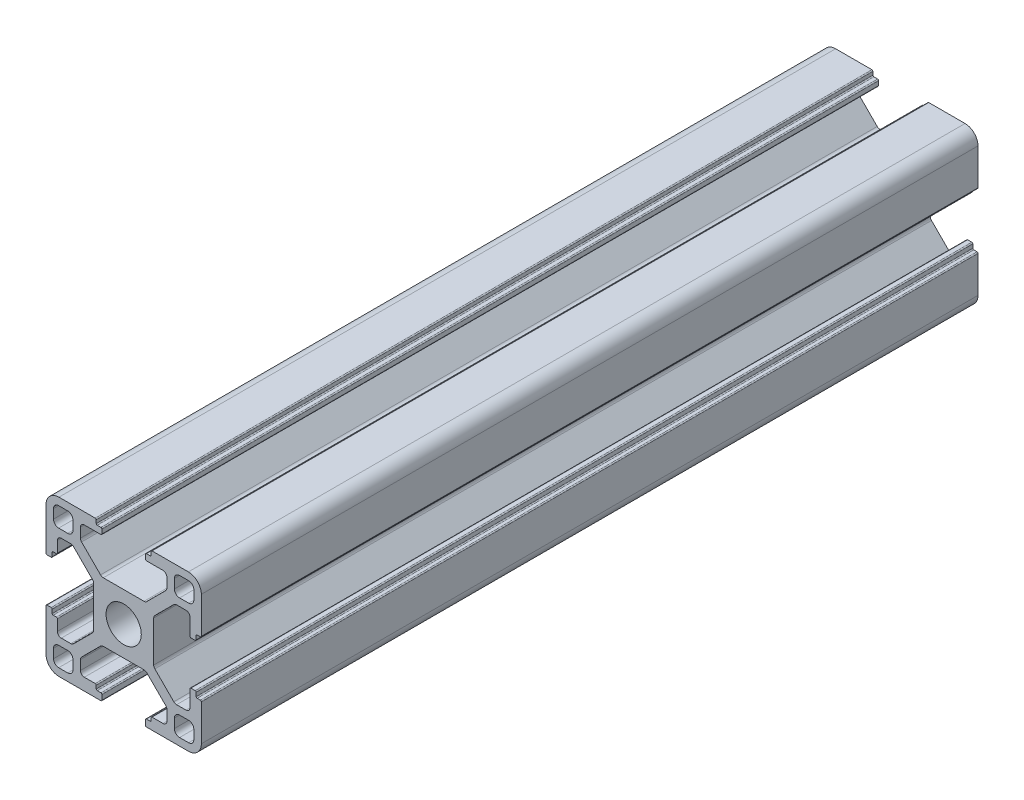
SolidWorks part; units mm, degrees
material "6063-T5"
ref_plane "Front Plane" through (0, 0, 0) normal (0, 0, 1) x (1, 0, 0)
ref_plane "Top Plane" through (0, 0, 0) normal (0, 1, 0) x (1, 0, 0)
ref_plane "Right Plane" through (0, 0, 0) normal (1, 0, 0) x (0, 0, -1)
sketch "Sketch1" plane through (0, 0, 0) normal (0, 0, 1) x (1, 0, 0)
  line L0 (0, 2.5) -> (0, 10.6)
  line L1 (2.5, 30) -> (9.5, 30)
  line L2 (30, 27.5) -> (30, 20.5)
  line L3 (27.5, 0) -> (19.4, 0)
  line L4 (19.464, 9.1128) -> (23.1303, 5.4465)
  line L5 (21.0197, 10.536) -> (24.686, 6.8697)
  line L6 (10.536, 21.0197) -> (6.8697, 24.686)
  line L7 (8.9803, 19.464) -> (5.314, 23.1303)
  line L8 (11.0663, 20.8) -> (18.9337, 20.8)
  line L9 (20.8, 18.9337) -> (20.8, 11.0663)
  line L10 (18.9337, 9.3324) -> (11.0663, 9.3324)
  line L11 (9.2, 11.0663) -> (9.2, 18.9337)
  line L12 (0, 19.4) -> (0, 27.5)
  line L13 (30, 9.5) -> (30, 2.5)
  line L14 (19.4, 27.8) -> (22.6, 27.8)
  line L15 (10.6, 27.8) -> (7.4, 27.8)
  line L16 (10.6, 0) -> (2.5, 0)
  line L17 (2.2, 20.5) -> (2.2, 22.6)
  line L18 (2.2, 9.5) -> (2.2, 7.4)
  line L19 (9.5, 2.3324) -> (7.4, 2.3324)
  line L20 (19.464, 21.0197) -> (23.1303, 24.686)
  line L21 (21.0197, 19.464) -> (24.686, 23.1303)
  line L22 (8.9803, 10.536) -> (5.314, 6.8697)
  line L23 (10.536, 9.1128) -> (6.8697, 5.4465)
  line L24 (10.8, 28.8) -> (10.8, 28)
  line L25 (19.2, 28.8) -> (19.2, 28)
  line L26 (0.2, 19.2) -> (1, 19.2)
  line L27 (0.2, 10.8) -> (1, 10.8)
  line L28 (28.8, 19.2) -> (28, 19.2)
  line L29 (28.8, 10.8) -> (28, 10.8)
  line L30 (10.8, 0.2) -> (10.8, 1.1324)
  line L31 (19.2, 0.2) -> (19.2, 1.1324)
  line L32 (20.5, 30) -> (27.5, 30)
  line L33 (27.8, 19.4) -> (27.8, 22.6)
  line L34 (27.8, 10.6) -> (27.8, 7.4)
  line L35 (20.5, 2.2) -> (22.6, 2.2)
  line L36 (6.65, 27.05) -> (6.65, 25.2163)
  line L37 (23.35, 27.05) -> (23.35, 25.2163)
  line L38 (2.95, 23.35) -> (4.7837, 23.35)
  line L39 (27.05, 23.35) -> (25.2163, 23.35)
  line L40 (2.95, 6.65) -> (4.7837, 6.65)
  line L41 (6.65, 3.0824) -> (6.65, 4.9161)
  line L42 (23.35, 2.95) -> (23.35, 4.9161)
  line L43 (27.05, 6.65) -> (25.2163, 6.65)
  line L44 (29, 10.6) -> (29, 9.9)
  line L45 (29.8, 20.3) -> (29.2, 20.3)
  line L46 (29, 20.1) -> (29, 19.4)
  line L47 (29.2, 9.7) -> (29.8, 9.7)
  line L48 (19.4, 29) -> (20.1, 29)
  line L49 (9.7, 29.8) -> (9.7, 29.2)
  line L50 (9.9, 29) -> (10.6, 29)
  line L51 (20.3, 29.2) -> (20.3, 29.8)
  line L52 (9.7, 2.1324) -> (9.7, 1.5324)
  line L53 (9.9, 1.3324) -> (10.6, 1.3324)
  line L54 (19.4, 1.3324) -> (20.1, 1.3324)
  line L55 (20.3, 1.5324) -> (20.3, 2)
  line L56 (2, 20.3) -> (1.4, 20.3)
  line L57 (1.2, 20.1) -> (1.2, 19.4)
  line L58 (1.2, 10.6) -> (1.2, 9.9)
  line L59 (1.4, 9.7) -> (2, 9.7)
  line L60 (27.55, 1.45) -> (25.8, 1.45)
  line L61 (24.8, 2.45) -> (24.8, 4.2)
  line L62 (25.8, 5.2) -> (27.55, 5.2)
  line L63 (28.55, 4.2) -> (28.55, 2.45)
  line L64 (24.8, 25.8) -> (24.8, 27.55)
  line L65 (25.8, 28.55) -> (27.55, 28.55)
  line L66 (28.55, 27.55) -> (28.55, 25.8)
  line L67 (27.55, 24.8) -> (25.8, 24.8)
  line L68 (2.45, 28.55) -> (4.2, 28.55)
  line L69 (5.2, 27.55) -> (5.2, 25.8)
  line L70 (1.45, 2.45) -> (1.45, 4.2)
  line L71 (2.45, 5.2) -> (4.2, 5.2)
  line L72 (5.2, 4.2) -> (5.2, 2.45)
  line L73 (4.2, 1.45) -> (2.45, 1.45)
  line L74 (4.2, 24.8) -> (2.45, 24.8)
  line L75 (1.45, 25.8) -> (1.45, 27.55)
  circle A0 centre (15, 15) radius 3.4
  arc A1 (25.8, 1.45) -> (24.8, 2.45) centre (25.8, 2.45) cw
  arc A2 (27.55, 1.45) -> (28.55, 2.45) centre (27.55, 2.45) ccw
  arc A3 (27.55, 5.2) -> (28.55, 4.2) centre (27.55, 4.2) cw
  arc A4 (24.8, 4.2) -> (25.8, 5.2) centre (25.8, 4.2) cw
  arc A5 (1.45, 2.45) -> (2.45, 1.45) centre (2.45, 2.45) ccw
  arc A6 (5.2, 2.45) -> (4.2, 1.45) centre (4.2, 2.45) cw
  arc A7 (4.2, 5.2) -> (5.2, 4.2) centre (4.2, 4.2) cw
  arc A8 (1.45, 4.2) -> (2.45, 5.2) centre (2.45, 4.2) cw
  arc A9 (24.8, 25.8) -> (25.8, 24.8) centre (25.8, 25.8) ccw
  arc A10 (28.55, 25.8) -> (27.55, 24.8) centre (27.55, 25.8) cw
  arc A11 (27.55, 28.55) -> (28.55, 27.55) centre (27.55, 27.55) cw
  arc A12 (24.8, 27.55) -> (25.8, 28.55) centre (25.8, 27.55) cw
  arc A13 (4.2, 28.55) -> (5.2, 27.55) centre (4.2, 27.55) cw
  arc A14 (5.2, 25.8) -> (4.2, 24.8) centre (4.2, 25.8) cw
  arc A15 (2.45, 24.8) -> (1.45, 25.8) centre (2.45, 25.8) cw
  arc A16 (2.45, 28.55) -> (1.45, 27.55) centre (2.45, 27.55) ccw
  arc A17 (30, 2.5) -> (27.5, 0) centre (27.5, 2.5) cw
  arc A18 (0, 2.5) -> (2.5, 0) centre (2.5, 2.5) ccw
  arc A19 (27.5, 30) -> (30, 27.5) centre (27.5, 27.5) cw
  arc A20 (0, 27.5) -> (2.5, 30) centre (2.5, 27.5) cw
  arc A21 (0, 10.6) -> (0.2, 10.8) centre (0.2, 10.6) cw
  arc A22 (1.2, 10.6) -> (1, 10.8) centre (1, 10.6) ccw
  arc A23 (2, 9.7) -> (2.2, 9.5) centre (2, 9.5) cw
  arc A24 (9.7, 2.1324) -> (9.5, 2.3324) centre (9.5, 2.1324) ccw
  arc A25 (10.6, 1.3324) -> (10.8, 1.1324) centre (10.6, 1.1324) cw
  arc A26 (10.6, 0) -> (10.8, 0.2) centre (10.6, 0.2) ccw
  arc A27 (19.4, 0) -> (19.2, 0.2) centre (19.4, 0.2) cw
  arc A28 (19.4, 1.3324) -> (19.2, 1.1324) centre (19.4, 1.1324) ccw
  arc A29 (20.3, 2) -> (20.5, 2.2) centre (20.5, 2) cw
  arc A30 (28, 10.8) -> (27.8, 10.6) centre (28, 10.6) ccw
  arc A31 (29, 10.6) -> (28.8, 10.8) centre (28.8, 10.6) ccw
  arc A32 (29.8, 9.7) -> (30, 9.5) centre (29.8, 9.5) cw
  arc A33 (28, 19.2) -> (27.8, 19.4) centre (28, 19.4) cw
  arc A34 (29, 19.4) -> (28.8, 19.2) centre (28.8, 19.4) cw
  arc A35 (30, 20.5) -> (29.8, 20.3) centre (29.8, 20.5) cw
  arc A36 (20.3, 29.8) -> (20.5, 30) centre (20.5, 29.8) cw
  arc A37 (19.4, 29) -> (19.2, 28.8) centre (19.4, 28.8) ccw
  arc A38 (19.2, 28) -> (19.4, 27.8) centre (19.4, 28) ccw
  arc A39 (10.8, 28) -> (10.6, 27.8) centre (10.6, 28) cw
  arc A40 (0, 19.4) -> (0.2, 19.2) centre (0.2, 19.4) ccw
  arc A41 (1.2, 19.4) -> (1, 19.2) centre (1, 19.4) cw
  arc A42 (2, 20.3) -> (2.2, 20.5) centre (2, 20.5) ccw
  arc A43 (10.6, 29) -> (10.8, 28.8) centre (10.6, 28.8) cw
  arc A44 (9.5, 30) -> (9.7, 29.8) centre (9.5, 29.8) cw
  arc A45 (1.4, 20.3) -> (1.2, 20.1) centre (1.4, 20.1) ccw
  arc A46 (20.1, 29) -> (20.3, 29.2) centre (20.1, 29.2) ccw
  arc A47 (9.7, 29.2) -> (9.9, 29) centre (9.9, 29.2) ccw
  arc A48 (29.2, 20.3) -> (29, 20.1) centre (29.2, 20.1) ccw
  arc A49 (29, 9.9) -> (29.2, 9.7) centre (29.2, 9.9) ccw
  arc A50 (20.1, 1.3324) -> (20.3, 1.5324) centre (20.1, 1.5324) ccw
  arc A51 (1.2, 9.9) -> (1.4, 9.7) centre (1.4, 9.9) ccw
  arc A52 (9.7, 1.5324) -> (9.9, 1.3324) centre (9.9, 1.5324) ccw
  arc A53 (23.35, 25.2163) -> (23.1303, 24.686) centre (22.6, 25.2163) cw
  arc A54 (25.2163, 23.35) -> (24.686, 23.1303) centre (25.2163, 22.6) ccw
  arc A55 (20.8, 18.9337) -> (21.0197, 19.464) centre (21.55, 18.9337) cw
  arc A56 (18.9337, 20.8) -> (19.464, 21.0197) centre (18.9337, 21.55) ccw
  arc A57 (6.65, 25.2163) -> (6.8697, 24.686) centre (7.4, 25.2163) ccw
  arc A58 (11.0663, 20.8) -> (10.536, 21.0197) centre (11.0663, 21.55) cw
  arc A59 (4.7837, 23.35) -> (5.314, 23.1303) centre (4.7837, 22.6) cw
  arc A60 (9.2, 18.9337) -> (8.9803, 19.464) centre (8.45, 18.9337) ccw
  arc A61 (4.7837, 6.65) -> (5.314, 6.8697) centre (4.7837, 7.4) ccw
  arc A62 (9.2, 11.0663) -> (8.9803, 10.536) centre (8.45, 11.0663) cw
  arc A63 (6.65, 4.9161) -> (6.8697, 5.4465) centre (7.4, 4.9161) cw
  arc A64 (11.0663, 9.3324) -> (10.536, 9.1128) centre (11.0663, 8.5824) ccw
  arc A65 (18.9337, 9.3324) -> (19.464, 9.1128) centre (18.9337, 8.5824) cw
  arc A66 (20.8, 11.0663) -> (21.0197, 10.536) centre (21.55, 11.0663) ccw
  arc A67 (25.2163, 6.65) -> (24.686, 6.8697) centre (25.2163, 7.4) cw
  arc A68 (23.35, 4.9161) -> (23.1303, 5.4465) centre (22.6, 4.9161) ccw
  arc A69 (7.4, 2.3324) -> (6.65, 3.0824) centre (7.4, 3.0824) cw
  arc A70 (22.6, 2.2) -> (23.35, 2.95) centre (22.6, 2.95) ccw
  arc A71 (27.8, 7.4) -> (27.05, 6.65) centre (27.05, 7.4) cw
  arc A72 (27.8, 22.6) -> (27.05, 23.35) centre (27.05, 22.6) ccw
  arc A73 (22.6, 27.8) -> (23.35, 27.05) centre (22.6, 27.05) cw
  arc A74 (2.2, 7.4) -> (2.95, 6.65) centre (2.95, 7.4) ccw
  arc A75 (2.2, 22.6) -> (2.95, 23.35) centre (2.95, 22.6) cw
  arc A76 (7.4, 27.8) -> (6.65, 27.05) centre (7.4, 27.05) ccw
  point P115 (0, 0)
extrude "Boss-Extrude1" add sketch "Sketch1" along normal blind 150
